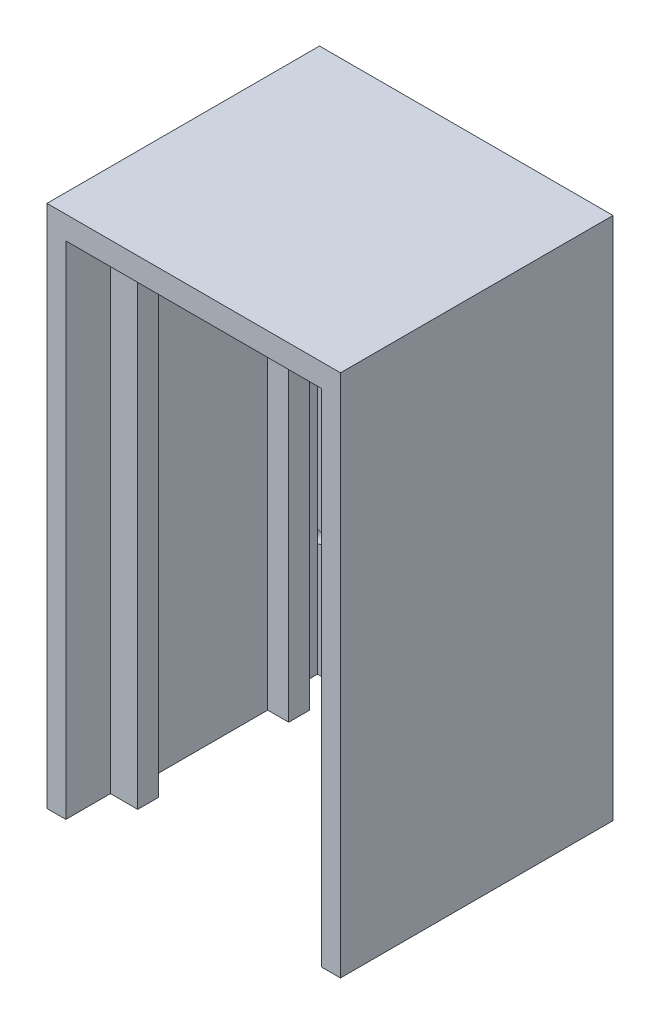
SolidWorks part; units mm, degrees
ref_plane "Front Plane" through (0, 0, 0) normal (0, 0, 1) x (1, 0, 0)
ref_plane "Top Plane" through (0, 0, 0) normal (0, 1, 0) x (1, 0, 0)
ref_plane "Right Plane" through (0, 0, 0) normal (1, 0, 0) x (0, 0, -1)
sketch "Sketch1" plane through (0, 0, 0) normal (0, 0, 1) x (-1, 0, 0)
  line L0 (-36, -71.0305) -> (36, -71.0305)
  line L1 (-36, -71.0305) -> (-36, 53.9695)
  line L2 (36, -71.0305) -> (36, 53.9695)
  line L3 (-36, 53.9695) -> (36, 53.9695)
  dimension "D1" = 125
  dimension "D2" = 72
extrude "Boss-Extrude1" add sketch "Sketch1" along normal blind 5
sketch "Sketch2" plane through (0, 0, 0) normal (0, 0, 1) x (-1, 0, 0)
  line L1 (34, 28.9695) -> (-34, 28.9695)
  line L2 (34, 28.9695) -> (34, -71.0305)
  line L3 (34, -71.0305) -> (-34, -71.0305)
  line L4 (-34, 28.9695) -> (-34, -71.0305)
  line L5 (34, 28.9695) -> (-34, -71.0305) construction
  line L6 (34, -71.0305) -> (-34, 28.9695) construction
  line L8 (30.5, 25.4695) -> (30.5, -67.5305)
  line L9 (30.5, -67.5305) -> (-30.5, -67.5305)
  line L10 (-30.5, 25.4695) -> (-30.5, -67.5305)
  line L11 (30.5, 25.4695) -> (-30.5, 25.4695)
  circle A0 centre (30.5, -67.5305) radius 1.5
  circle A1 centre (-30.5, -67.5305) radius 1.5
  circle A2 centre (30.5, 25.4695) radius 1.5
  circle A3 centre (-30.5, 25.4695) radius 1.5
  circle A4 centre (0, -21.0305) radius 1.5
  point P0 (0, -21.0305)
  dimension "D6" = 3
  dimension "D7" = 3
  dimension "D8" = 3
  dimension "D9" = 3
  dimension "D1" = 68
  dimension "D3" = 100
  dimension "D5" = 3.5
extrude "Cut-Extrude6" cut sketch "Sketch2" along normal blind 5 contours A0 | A1 | A4 | A3 | A2
sketch "Sketch3" plane through (0, 0, 5) normal (0, 0, 1) x (1, 0, 0)
  line L4 (-30.5, -48.4695) -> (-30.5, -53.9695)
  line L5 (-36, -53.9695) -> (36, -53.9695) construction
  line L6 (30.5, -48.4695) -> (30.5, -53.9695)
  line L8 (30.5, -48.4695) -> (30.5, 65.5305)
  line L9 (30.5, 65.5305) -> (-30.5, 65.5305)
  line L10 (-30.5, 65.5305) -> (-30.5, -48.4695)
  line L11 (-30.5, -48.4695) -> (30.5, -48.4695)
  line L12 (30.5, -48.4695) -> (30.5, 65.5305)
  line L13 (30.5, 65.5305) -> (-30.5, 65.5305)
  line L14 (-30.5, 65.5305) -> (-30.5, -48.4695)
  line L15 (-30.5, -48.4695) -> (30.5, -48.4695)
  circle M5 centre (-30.5, -25.4695) radius 1.5
  circle M6 centre (30.5, -25.4695) radius 1.5
  circle M8 centre (30.5, 67.5305) radius 1.5
  circle M9 centre (-30.5, 67.5305) radius 1.5
  line M10 (36, -53.9695) -> (36, 71.0305)
  line M11 (36, 71.0305) -> (-36, 71.0305)
  line M12 (-36, 71.0305) -> (-36, -53.9695)
  line M13 (-36, -53.9695) -> (36, -53.9695)
  dimension "D1" = 5.5
extrude "Boss-Extrude2" add sketch "Sketch3" along normal blind 60 contours L14 L13 L12 L6 L4 M6 M13 M10 M11 M12 M5 M8 M9 | L12 M6 | L14 M5 | M9 | M8
sketch "Sketch4" plane through (0, -53.9695, 0) normal (0, -1, 0) x (1, 0, 0)
  line L8 (-29, 18.3563) -> (29, 18.3563)
  line L9 (-29, 18.3563) -> (-29, 49.3563)
  line L10 (-29, 49.3563) -> (29, 49.3563)
  line L11 (29, 18.3563) -> (29, 49.3563)
  line L12 (-29, 18.3563) -> (29, 49.3563) construction
  line L13 (-29, 49.3563) -> (29, 18.3563) construction
  line L14 (-34, 13.3563) -> (-34, 54.3563)
  line L15 (-34, 54.3563) -> (34, 54.3563)
  line L16 (34, 13.3563) -> (34, 54.3563)
  line L17 (-34, 13.3563) -> (34, 13.3563)
  line L19 (-24, 13.3563) -> (24, 13.3563)
  line L20 (-24, 13.3563) -> (-24, 54.3563)
  line L21 (-24, 54.3563) -> (24, 54.3563)
  line L22 (24, 13.3563) -> (24, 54.3563)
  line L23 (-24, 13.3563) -> (24, 54.3563) construction
  line L24 (-24, 54.3563) -> (24, 13.3563) construction
  point P4 (0, 33.8563)
  point P8 (0, 33.8563)
  line M8 (30.5, 65) -> (30.5, 5)
  line M10 (-30.5, 5) -> (-30.5, 65)
  dimension "D1" = 5
  dimension "D2" = 5
  dimension "D3" = 58
  dimension "D4" = 0
  dimension "D5" = 31
extrude "Boss-Extrude3" add sketch "Sketch4" against normal up to surface (119.5 mm away) contours L17 L20 L8 L9 L10 L15 M10 | L22 L17 L15 L10 L11 L8 M8 up to face at (0, 65.5305, 35)
sketch "Sketch5" plane through (0, 71.0305, 0) normal (0, 1, 0) x (1, 0, 0)
  line L0 (36, -65) -> (-36, -65) construction
  line L1 (-40, 0) -> (40, 0)
  line L2 (-40, 0) -> (-40, -65)
  line L3 (-40, -65) -> (40, -65)
  line L4 (40, 0) -> (40, -65)
  line L5 (36, 0) -> (-36, 0) construction
  line L6 (-36, -65) -> (-36, 0) construction
  line L7 (-35, 0) -> (35, 0)
  line L8 (-35, 0) -> (-35, -65)
  line L9 (-35, -65) -> (35, -65)
  line L10 (35, 0) -> (35, -65)
  line L11 (36, -65) -> (36, 0) construction
  line M9 (36, 0) -> (-36, 0)
  line M10 (-36, 0) -> (-36, -65)
  line M11 (-36, -65) -> (36, -65)
  line M12 (36, -65) -> (36, 0)
  dimension "D1" = 0
  dimension "D2" = 0
  dimension "D3" = 1
  dimension "D4" = 1
  dimension "D5" = 4
  dimension "D6" = 4
extrude "Cut-Extrude7" cut sketch "Sketch5" against normal blind 158 contours L8 M9 M10 M11 | L2 L3 L1 M10 | L4 L1 L3 M12 | L10 M9 M11 M12
